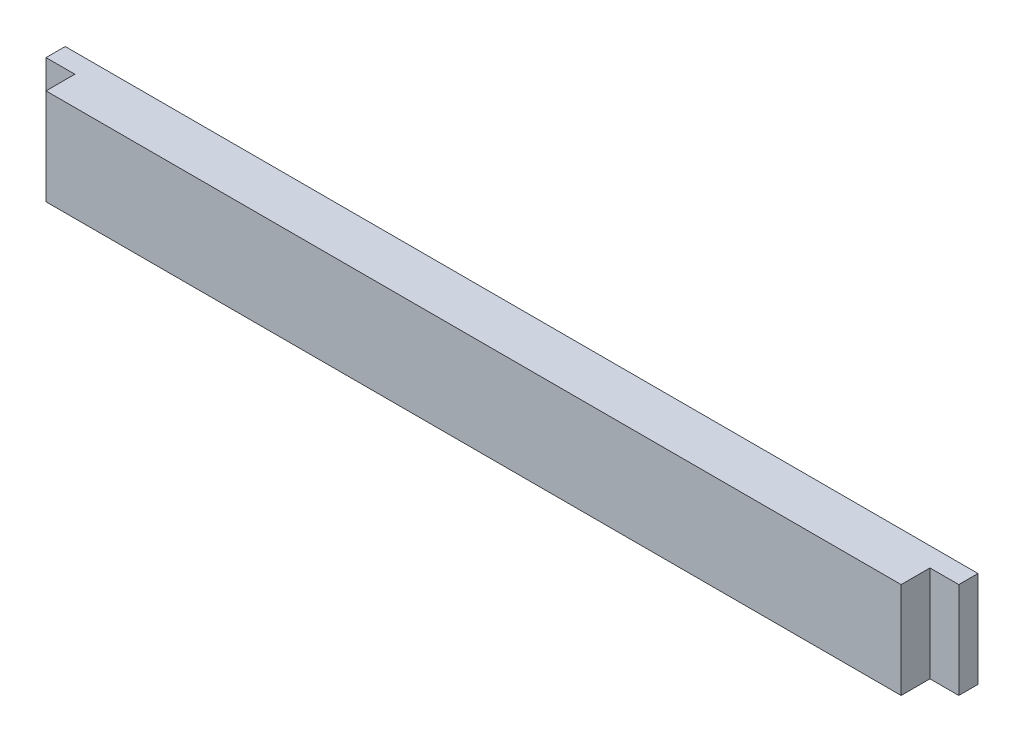
SolidWorks part; units mm, degrees
ref_plane "Plan de face" through (0, 0, 0) normal (0, 0, 1) x (1, 0, 0)
ref_plane "Plan de dessus" through (0, 0, 0) normal (0, 1, 0) x (1, 0, 0)
ref_plane "Plan de droite" through (0, 0, 0) normal (1, 0, 0) x (0, 0, -1)
sketch "Esquisse1" plane through (0, 0, 0) normal (0, 0, 1) x (1, 0, 0)
  line L1 (-95, 10) -> (95, 10)
  line L2 (-95, 10) -> (-95, -10)
  line L3 (-95, -10) -> (95, -10)
  line L4 (95, 10) -> (95, -10)
  dimension "D1" = 20
  dimension "D2" = 190
  dimension "D3" = 95
  dimension "D4" = 10
extrude "Boss.-Extru.1" add sketch "Esquisse1" along normal blind 10
sketch "Esquisse2" plane through (0, 0, 10) normal (0, 0, 1) x (1, 0, 0)
  line L0 (-95, -10) -> (95, -10) construction
  line L1 (-95, 10) -> (-89, 10)
  line L2 (-95, 10) -> (-95, -10)
  line L3 (-95, -10) -> (-89, -10)
  line L4 (-89, 10) -> (-89, -10)
  line L5 (0, 44.6188) -> (0, -56.7962) construction
  line L6 (89, 10) -> (89, -10)
  line L7 (95, -10) -> (89, -10)
  line L8 (95, 10) -> (95, -10)
  line L9 (95, 10) -> (89, 10)
  dimension "D1" = 6
extrude "Enlèv. mat.-Extru.1" cut sketch "Esquisse2" against normal blind 6
sketch "Esquisse3" plane through (0, 0, 0) normal (0, 0, -1) x (-1, 0, 0)
  line L0 (-95, 10) -> (95, 10) construction
  line L1 (95, 10) -> (95, -10) construction
  circle A0 centre (92, 0) radius 1.5
  dimension "D1" = 3
  dimension "D2" = 10
  dimension "D3" = 3
extrude "Enlèv. mat.-Extru.2" cut sketch "Esquisse3" against normal blind 6
equation "\"D3@Esquisse1\"=\"D2@Esquisse1\"/2"
equation "\"D4@Esquisse1\"=\"D1@Esquisse1\"/2"
